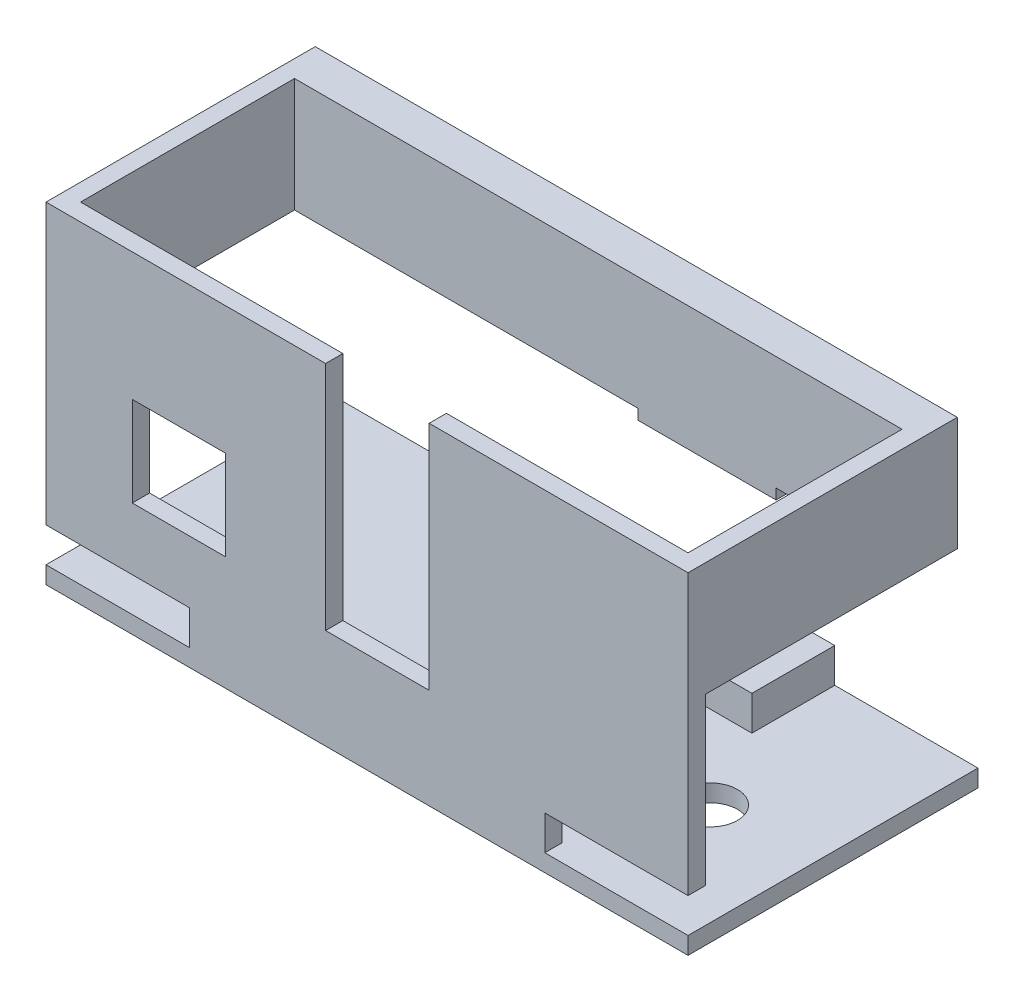
SolidWorks part; units mm, degrees
ref_plane "Front" through (0, 0, 0) normal (0, 0, 1) x (1, 0, 0)
ref_plane "Top" through (0, 0, 0) normal (0, 1, 0) x (1, 0, 0)
ref_plane "Right" through (0, 0, 0) normal (1, 0, 0) x (0, 0, -1)
sketch "Sketch1" plane through (0, 0, 0) normal (0, 0, 1) x (1, 0, 0)
  line L0 (-1.25, 0) -> (-1.25, 24)
  line L1 (-1.25, 0) -> (45.25, 0)
  line L2 (0, 0) -> (0, 22.75) construction
  line L3 (-1.25, 22.75) -> (45.25, 22.75) construction
  line L4 (44, 0) -> (44, 22.75) construction
  line L5 (45.25, 0) -> (45.25, 24)
  line L6 (-1.25, 24) -> (45.25, 24)
  line L7 (-1.25, 0) -> (-1.25, 22.75) construction
  line L8 (45.25, 0) -> (45.25, 22.75) construction
  dimension "D1" = 44
  dimension "D2" = 22.75
  dimension "D5" = 46.5
  dimension "D3" = 1.25
  dimension "D4" = 1.25
  dimension "D6" = 1.25
extrude "Boss-Extrude1" add sketch "Sketch1" against normal blind 21
shell "Shell1" thickness 1.25
sketch "Sketch2" plane through (-1.25, 0, 0) normal (-1, 0, 0) x (0, 0, 1)
  line L0 (-1.25, 24) -> (-1.25, 1.25) construction
  line L1 (-21, 1.25) -> (-1.25, 1.25)
  line L2 (-21, 1.25) -> (-21, 15.75)
  line L3 (-21, 15.75) -> (-1.25, 15.75)
  line L4 (-1.25, 1.25) -> (-1.25, 15.75)
  dimension "D1" = 14.5
extrude "Cut-Extrude1" cut sketch "Sketch2" against normal through all
sketch "Sketch4" plane through (0, 0, 0) normal (0, 0, 1) x (1, 0, 0)
  line L0 (-1.25, 1.25) -> (45.25, 1.25) construction
  line L1 (5, 14.75) -> (11.75, 14.75)
  line L2 (5, 14.75) -> (5, 8.25)
  line L3 (5, 8.25) -> (11.75, 8.25)
  line L4 (11.75, 14.75) -> (11.75, 8.25)
  line L5 (19, 24.25) -> (26.5, 24.25)
  line L6 (19, 24.25) -> (19, 7.25)
  line L7 (19, 7.25) -> (26.5, 7.25)
  line L8 (26.5, 24.25) -> (26.5, 7.25)
  line L11 (0, 24) -> (0, 15.75) construction
  dimension "D1" = 7
  dimension "D2" = 6
  dimension "D3" = 13.5
  dimension "D4" = 6.5
  dimension "D5" = 11.75
  dimension "D6" = 5
  dimension "D7" = 6.75
  dimension "D8" = 19
  dimension "D9" = 26.5
  dimension "D10" = 7.5
  dimension "D11" = 23
  dimension "D12" = 17
extrude "Cut-Extrude3" cut sketch "Sketch4" against normal up to surface (1.25 mm away) up to face at (22, 14.1875, -1.25)
sketch "Sketch6" plane through (0, 0, 0) normal (0, -1, 0) x (-1, 0, 0)
  line L0 (1.25, 0) -> (-45.25, 0) construction
  line L1 (-22, 0) -> (-22, 5.6918) construction
  circle A0 centre (-37.875, 9) radius 1.95
  circle A1 centre (-6.125, 9) radius 1.95
  dimension "D1" = 3.9
  dimension "D2" = 9
  dimension "D3" = 31.75
extrude "Cut-Extrude4" cut sketch "Sketch6" against normal up to surface (1.25 mm away) contours A1 | A0
sketch "Sketch7" plane through (0, 0, 0) normal (0, 0, 1) x (1, 0, 0)
  line L0 (45.25, 0) -> (45.25, 24) construction
  line L1 (45.25, 1.25) -> (34.875, 1.25)
  line L2 (45.25, 1.25) -> (45.25, 3.75)
  line L3 (45.25, 3.75) -> (34.875, 3.75)
  line L4 (34.875, 1.25) -> (34.875, 3.75)
  line L5 (-1.25, 0) -> (45.25, 0) construction
  line L6 (35.925, 0) -> (39.825, 0) construction
  line L7 (35.925, 0) -> (39.825, 0) construction
  line L8 (37.875, 0) -> (37.875, 1.5787) construction
  line L9 (22, 0) -> (22, 4.652) construction
  line L10 (9.125, 1.25) -> (9.125, 3.75)
  line L11 (-1.25, 3.75) -> (9.125, 3.75)
  line L12 (-1.25, 1.25) -> (-1.25, 3.75)
  line L13 (-1.25, 1.25) -> (9.125, 1.25)
  dimension "D1" = 1.25
  dimension "D2" = 3
  dimension "D3" = 2.5
extrude "Cut-Extrude5" cut sketch "Sketch7" against normal up to surface (1.25 mm away) up to face at (22.25, 14.6667, -1.25)
sketch "Sketch9" plane through (0, 1.25, 0) normal (0, 1, 0) x (1, 0, 0)
  line L0 (-1.25, 21) -> (45.25, 21) construction
  line L1 (34.875, 21) -> (15.375, 21)
  line L2 (34.875, 21) -> (34.875, 15)
  line L3 (34.875, 15) -> (15.375, 15)
  line L4 (15.375, 21) -> (15.375, 15)
  line L6 (34.875, 1.25) -> (34.875, 21) construction
  dimension "D1" = 6
  dimension "D2" = 19.5
extrude "Boss-Extrude3" add sketch "Sketch9" along normal blind 2.5
sketch "Sketch12" plane through (45.25, 0, 0) normal (1, 0, 0) x (0, 0, -1)
  line L1 (1.25, 15.75) -> (21, 15.75) construction
  line L2 (21, 24) -> (19.5, 24)
  line L3 (21, 24) -> (21, 15.75)
  line L4 (21, 15.75) -> (19.5, 15.75)
  line L5 (19.5, 24) -> (19.5, 15.75)
  dimension "D1" = 1.5
extrude "Cut-Extrude7" cut sketch "Sketch12" along normal through all and the other way through all from surface at -45.25 starting at face at (0, 19.875, -11.125)
sketch "Sketch13" plane through (0, 0, 0) normal (1, 0, 0) x (0, 0, -1)
  line L0 (1.25, 15.75) -> (19.5, 15.75) construction
  line L1 (19.5, 24) -> (16.75, 24)
  line L2 (19.5, 24) -> (19.5, 15.75)
  line L3 (19.5, 15.75) -> (16.75, 15.75)
  line L4 (16.75, 24) -> (16.75, 15.75)
  dimension "D1" = 2.75
extrude "Boss-Extrude4" add sketch "Sketch13" along normal up to vertex (44 mm away) contours L4 L3 L2 L1
sketch "Sketch15" plane through (0, 15.75, 0) normal (0, -1, 0) x (1, 0, 0)
  line L0 (-1.25, -19.5) -> (45.25, -19.5) construction
  line L1 (34.875, -19.5) -> (24.875, -19.5)
  line L2 (34.875, -19.5) -> (34.875, -16.75)
  line L3 (34.875, -16.75) -> (24.875, -16.75)
  line L4 (24.875, -19.5) -> (24.875, -16.75)
  line L5 (44, -16.75) -> (0, -16.75) construction
  line L6 (34.875, -15) -> (34.875, -21) construction
  dimension "D1" = 10
extrude "Boss-Extrude5" add sketch "Sketch15" along normal blind 0.75 contours L1 L4 L3 L2
